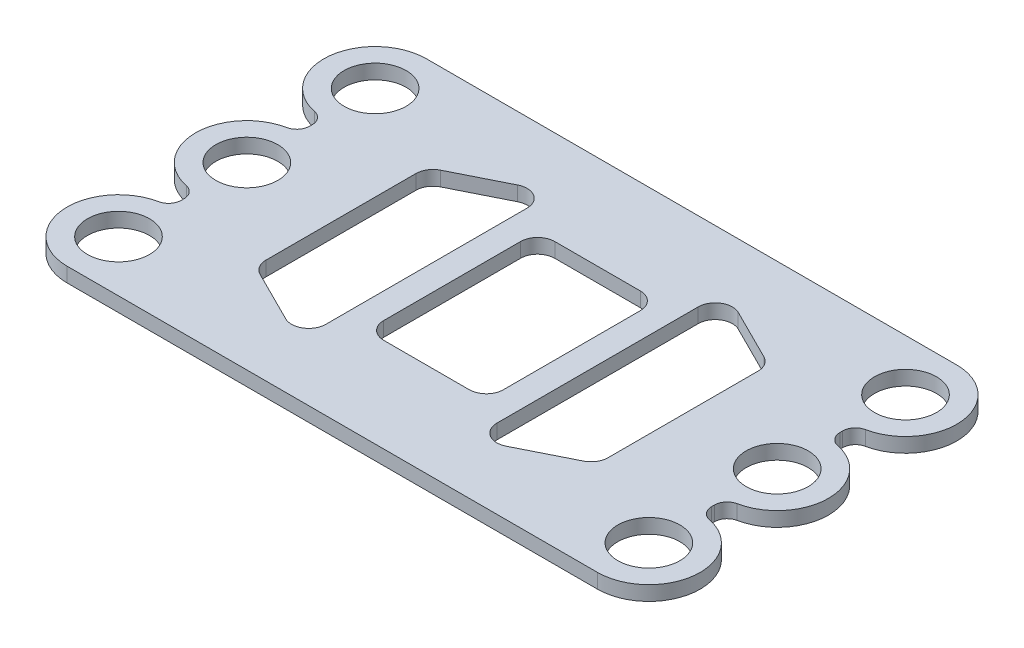
SolidWorks part; units mm, degrees
ref_plane "Front Plane" through (0, 0, 0) normal (0, 0, 1) x (1, 0, 0)
ref_plane "Top Plane" through (0, 0, 0) normal (0, 1, 0) x (1, 0, 0)
ref_plane "Right Plane" through (0, 0, 0) normal (1, 0, 0) x (0, 0, -1)
sketch "Sketch1" plane through (0, 0, 0) normal (0, 1, 0) x (1, 0, 0)
  line L0 (-31.5664, 0) -> (27.1678, 0) construction
  line L1 (0, 65.0734) -> (0, -26.7797) construction
  line L2 (31, 21) -> (31, 9) construction
  line L3 (-37, 21) -> (37, 21)
  line L4 (-37, 21) -> (-37, -21)
  line L5 (-37, -21) -> (37, -21)
  line L6 (37, 21) -> (37, -21)
  line L7 (-37, 21) -> (37, -21) construction
  line L8 (-37, -21) -> (37, 21) construction
  line L17 (31, 9) -> (31, 6)
  line L18 (31, -6) -> (31, -9)
  line L19 (-31, 9) -> (-31, 6)
  line L20 (-31, -6) -> (-31, -9)
  circle A0 centre (31, 15) radius 6
  circle A1 centre (31, 0) radius 6
  circle A2 centre (31, -15) radius 6
  circle A3 centre (-31, -15) radius 6
  circle A4 centre (-31, 0) radius 6
  circle A5 centre (-31, 15) radius 6
  circle A6 centre (-31, 15) radius 3.625
  circle A7 centre (-31, 0) radius 3.625
  circle A8 centre (-31, -15) radius 3.625
  circle A9 centre (31, -15) radius 3.625
  circle A10 centre (31, 0) radius 3.625
  circle A11 centre (31, 15) radius 3.625
  point P4 (0, 0)
  dimension "D3" = 12
  dimension "D8" = 7.25
  dimension "D1" = 74
  dimension "D4" = 42
extrude "Boss-Extrude1" add sketch "Sketch1" along normal blind 1.7
sketch "Sketch2" plane through (0, 1.7, 0) normal (0, 1, 0) x (1, 0, 0)
  line L0 (0, 21) -> (0, -21) construction
  line L1 (-31, 21) -> (31, 21) construction
  line L2 (-31, -21) -> (31, -21) construction
  line L3 (10, 15) -> (20, 10)
  line L4 (-10, 15) -> (10, 15)
  line L5 (-10, 15) -> (-10, -15)
  line L6 (-10, -15) -> (10, -15)
  line L7 (10, 15) -> (10, -15)
  line L8 (-10, 15) -> (10, -15) construction
  line L9 (-10, -15) -> (10, 15) construction
  line L10 (-20, 10) -> (20, 10)
  line L11 (-20, 10) -> (-20, -10)
  line L12 (-20, -10) -> (20, -10)
  line L13 (20, 10) -> (20, -10)
  line L14 (-20, 10) -> (20, -10) construction
  line L15 (-20, -10) -> (20, 10) construction
  line L16 (20, -10) -> (10, -15)
  line L17 (10, -15) -> (9.9535, -15.0074)
  line L18 (-10, -15) -> (-20, -10)
  line L19 (-20, 10) -> (-10, 15)
  line L21 (-7, 10) -> (7, 10)
  line L22 (-7, 10) -> (-7, -10)
  line L23 (-7, -10) -> (7, -10)
  line L24 (7, 10) -> (7, -10)
  line L25 (-7, 10) -> (7, -10) construction
  line L26 (-7, -10) -> (7, 10) construction
  point P6 (0, 0)
  point P12 (0, 0)
  point P17 (0, 0)
  dimension "D1" = 20
  dimension "D2" = 30
  dimension "D3" = 20
  dimension "D4" = 40
  dimension "D5" = 3
extrude "Cut-Extrude1" cut sketch "Sketch2" against normal up to next contours L11 L12 L5 L10 | L19 L10 L5 | L18 L5 L12 | L16 L12 L7 | L13 L10 L7 L12 | L7 L10 L3 | L24 L10 L22 L12
fillet "Fillet1" radius 1.5 8 edges at (31, 0.85, 9) (31, 0.85, 6) (31, 0.85, -6) (31, 0.85, -9) (-31, 0.85, 9) (-31, 0.85, 6) (-31, 0.85, -6) (-31, 0.85, -9)
fillet "Fillet2" radius 2 12 edges at (20, 0.85, 10) (-10, 0.85, 15) (-10, 0.85, -15) (20, 0.85, -10) (10, 0.85, 15) (-20, 0.85, 10) (10, 0.85, -15) (-20, 0.85, -10) (7, 0.85, 10) (-7, 0.85, 10) (7, 0.85, -10) (-7, 0.85, -10)
